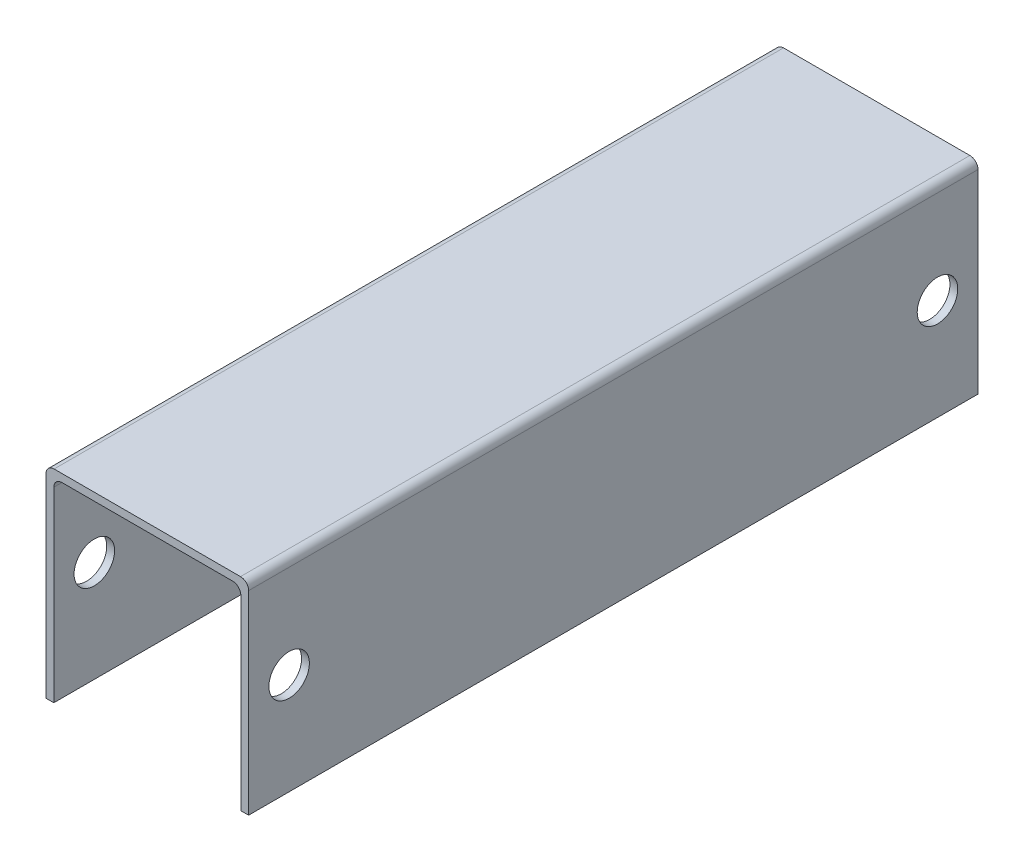
SolidWorks part; units mm, degrees
material "AISI 304"
ref_plane "Front Plane" through (0, 0, 0) normal (0, 0, 1) x (1, 0, 0)
ref_plane "Top Plane" through (0, 0, 0) normal (0, 1, 0) x (1, 0, 0)
ref_plane "Right Plane" through (0, 0, 0) normal (1, 0, 0) x (0, 0, -1)
sketch "Sketch1" plane through (0, 0, 0) normal (0, 0, 1) x (1, 0, 0)
  line L0 (0, 0) -> (0, 50)
  line L1 (0, 50) -> (50, 50)
  line L2 (50, 50) -> (50, 0)
  line L3 (50, 0) -> (48.0722, 0)
  line L4 (48.0722, 0) -> (48.0722, 48.0722)
  line L5 (48.0722, 48.0722) -> (1.9278, 48.0722)
  line L6 (1.9278, 48.0722) -> (1.9278, 0)
  line L7 (1.9278, 0) -> (0, 0)
  line L8 (1.9278, 48.0722) -> (1.9278, 50) construction
  dimension "D1" = 50
  dimension "D2" = 1.9278
extrude "Boss-Extrude1" add sketch "Sketch1" along normal blind 180
sketch "Sketch2" plane through (0, 0, 0) normal (-1, 0, 0) x (0, 0, 1)
  line L0 (0, 50) -> (0, 0) construction
  line L1 (180, 50) -> (180, 0) construction
  circle A0 centre (10, 25) radius 5
  circle A1 centre (170, 25) radius 5
  point P8 (0, 25)
  dimension "D3" = 10
  dimension "D1" = 10
  dimension "D2" = 10
extrude "Cut-Extrude1" cut sketch "Sketch2" against normal through all
fillet "Fillet1" radius 2 4 edges at (1.9278, 48.0722, 90) (48.0722, 48.0722, 90) (0, 50, 90) (50, 50, 90)
